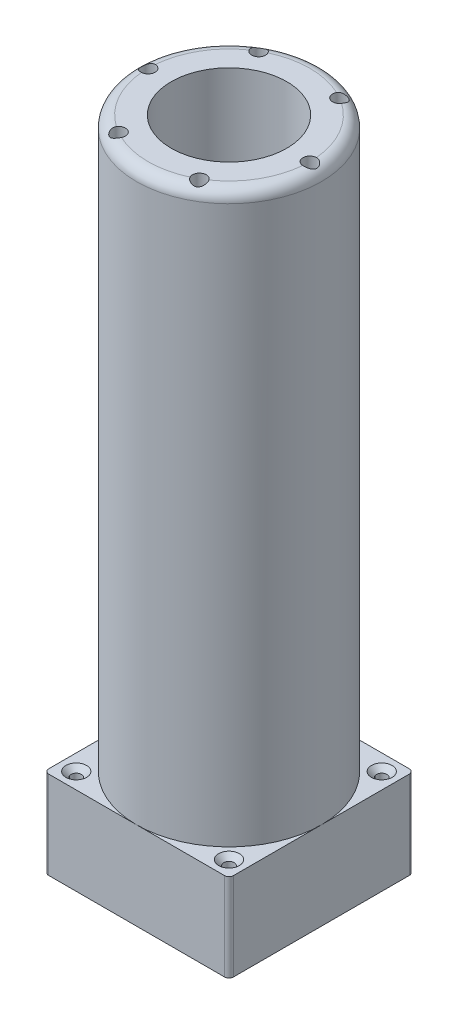
SolidWorks part; units mm, degrees
ref_plane "Płaszczyzna przednia" through (0, 0, 0) normal (0, 0, 1) x (1, 0, 0)
ref_plane "Płaszczyzna górna" through (0, 0, 0) normal (0, 1, 0) x (1, 0, 0)
ref_plane "Płaszczyzna prawa" through (0, 0, 0) normal (1, 0, 0) x (0, 0, -1)
sketch "Szkic1" plane through (0, 0, 0) normal (0, 1, 0) x (1, 0, 0)
  line L1 (-38, -40) -> (38, -40)
  line L2 (-40, -38) -> (-40, 38)
  line L3 (-38, 40) -> (38, 40)
  line L4 (40, -38) -> (40, 38)
  line L5 (-40, -40) -> (40, 40) construction
  line L6 (-40, 40) -> (40, -40) construction
  arc A0 (38, -40) -> (40, -38) centre (38, -38) ccw
  arc A1 (-38, -40) -> (-40, -38) centre (-38, -38) cw
  arc A2 (-40, 38) -> (-38, 40) centre (-38, 38) cw
  arc A3 (38, 40) -> (40, 38) centre (38, 38) cw
  point P0 (0, 0)
  dimension "D3" = 2
  dimension "D1" = 80
  dimension "D2" = 80
extrude "Dodanie-wyciągnięcie1" add sketch "Szkic1" along normal blind 38
sketch "Szkic2" plane through (0, 38, 0) normal (0, 1, 0) x (1, 0, 0)
  circle A0 centre (0, 0) radius 40
  dimension "D1" = 80
extrude "Dodanie-wyciągnięcie2" add sketch "Szkic2" along normal blind 246
sketch "Szkic3" plane through (0, 38, 0) normal (0, 1, 0) x (1, 0, 0)
  line L0 (0, 0) -> (43.5477, -43.5477) construction
  circle A0 centre (33.0503, -33.0503) radius 2
  arc A1 (38, -40) -> (40, -38) centre (38, -38) ccw construction
  circle A2 centre (-33.0503, -33.0503) radius 2
  circle A3 centre (-33.0503, 33.0503) radius 2
  circle A4 centre (33.0503, 33.0503) radius 2
  point P8 (39.4142, -39.4142)
  point P18 (0, 0)
  dimension "D1" = 4
  dimension "D2" = 7
  dimension "D3" = 4
hole_wizard "Pogłębienie stożkowe pod M4 Wkręt z łbem stożkowym płaskim1" positions "Szkic4" profile "Szkic5" countersink size "M4" standard "ISO" end condition through all
sketch "Szkic4" plane through (0, 38, 0) normal (0, 1, 0) x (1, 0, 0)
  point P0 (-33.0503, 33.0503)
  point P3 (33.0503, 33.0503)
  point P6 (33.0503, -33.0503)
  point P9 (-33.0503, -33.0503)
sketch "Szkic5" plane through (-33.0503, 38, -33.0503) normal (1, 0, 0) x (0, 0, 1)
  line L0 (0, 0) -> (0, 38)
  line L1 (0, 38) -> (2.25, 38)
  line L2 (2.25, 38) -> (2.25, 2.23)
  line L3 (2.25, 2.23) -> (4.48, 0)
  line L5 (4.48, 0) -> (0, 0)
  line L6 (-2.25, 2.23) -> (-4.48, 0) construction
  line L11 (0, -6.35) -> (0, 107.95) construction
  dimension "Średnica otworu na wylot" = 4.5
  dimension "Głębokość otworu na wylot" = 38
  dimension "Średnica zewnętrznego pogłębienia stożkowego" = 8.96
  dimension "Kąt zewnętrznego pogłębienia stożkowego" = 90
sketch "Szkic6" plane through (0, 284, 0) normal (0, 1, 0) x (1, 0, 0)
  circle A0 centre (0, 0) radius 25
  dimension "D1" = 50
extrude "Wytnij-wyciągnięcie1" cut sketch "Szkic6" against normal through all
fillet "Zaokrąglenie1" radius 5 1 edges at (0, 284, 40)
sketch "Szkic7" plane through (0, 284, 0) normal (0, 1, 0) x (1, 0, 0)
  line L0 (-69.84, 0) -> (58.4603, 0) construction
  circle A1 centre (-35, 0) radius 3
  circle A2 centre (0, 0) radius 35 construction
  circle A3 centre (-17.5, 30.3109) radius 3
  circle A4 centre (17.5, 30.3109) radius 3
  circle A5 centre (35, 0) radius 3
  circle A6 centre (17.5, -30.3109) radius 3
  circle A7 centre (-17.5, -30.3109) radius 3
  point P20 (0, 0)
  dimension "D1" = 6
  dimension "D2" = 6
hole_wizard "Otwory ustalające Ø6.0mm1" positions "Szkic8" profile "Szkic9" hole size "Ø6.0" standard "ISO"
sketch "Szkic8" plane through (0, 284, 0) normal (0, 1, 0) x (1, 0, 0)
  point P0 (-17.5, 30.3109)
  point P3 (17.5, 30.3109)
  point P6 (35, 0)
  point P9 (17.5, -30.3109)
  point P12 (-17.5, -30.3109)
  point P15 (-35, 0)
sketch "Szkic9" plane through (-17.5, 284, -30.3109) normal (1, 0, 0) x (0, 0, 1)
  line L0 (0, 0) -> (0, 36.8026)
  line L1 (0, 36.8026) -> (3, 35)
  line L2 (3, 35) -> (3, 0)
  line L5 (3, 0) -> (0, 0)
  line L10 (0, 36.8026) -> (-3, 35) construction
  line L11 (0, -6.35) -> (0, 107.95) construction
  dimension "Średnica otworu" = 6
  dimension "Głębokość otworu" = 35
  dimension "Kąt wiertła" = 118
